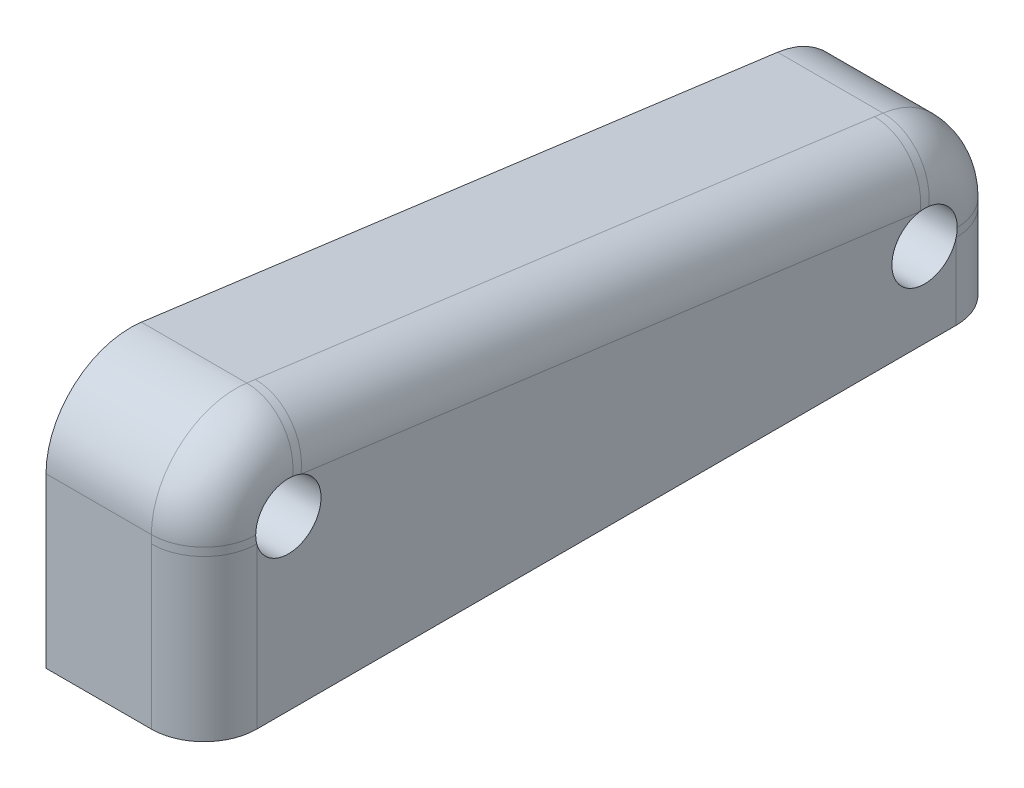
SolidWorks part; units mm, degrees
ref_plane "Plan de face" through (0, 0, 0) normal (0, 0, 1) x (1, 0, 0)
ref_plane "Plan de dessus" through (0, 0, 0) normal (0, 1, 0) x (1, 0, 0)
ref_plane "Plan de droite" through (0, 0, 0) normal (1, 0, 0) x (0, 0, -1)
sketch "Esquisse1" plane through (0, 0, 0) normal (1, 0, 0) x (0, 0, -1)
  line L0 (0, 0) -> (-76.3723, 0)
  line L1 (-76.3723, 0) -> (-76.3723, 25.1202)
  line L2 (-76.3723, 25.1202) -> (0, 15)
  line L3 (0, 15) -> (0, 0)
  line L4 (-68.3723, 16) -> (-8, 8) construction
  circle A0 centre (-68.3723, 16) radius 3.1
  circle A1 centre (-8, 8) radius 3.1
  dimension "D1" = 6.2
  dimension "D2" = 60.9
  dimension "D3" = 8
  dimension "D4" = 8
  dimension "D5" = 8
  dimension "D6" = 8
  dimension "D7" = 15
extrude "Boss.-Extru.1" add sketch "Esquisse1" along normal blind 15
fillet "Congé1" radius 8 2 edges at (7.5, 15, 0) (7.5, 25.1202, 76.3723)
fillet "Congé2" radius 5 3 edges at (15, 3.9951, 0) (15, 7.9951, 76.3723) (15, 19.9208, 37.1352)
sketch "Esquisse2" plane through (0, 0, 0) normal (-1, 0, 0) x (0, 0, 1)
  line L0 (60.5168, 17.9755) -> (15.0698, 11.9532)
  line L3 (71.3723, 5) -> (71.3723, 8.476)
  line L4 (67.3214, 23.9208) -> (6.9491, 15.9208)
  line L5 (0, 7.9902) -> (0, 0)
  line L6 (0, 0) -> (76.3723, 0)
  line L7 (76.3723, 0) -> (76.3723, 15.9902)
  line L11 (76.3723, 14.7311) -> (76.3723, 15.9902)
  line L12 (8.4177, 11.0717) -> (7.6059, 10.9642)
  line L13 (67.9782, 18.9642) -> (7.6059, 10.9642) construction
  line L14 (0, 7.9902) -> (0, 0) construction
  line L15 (0, 0) -> (76.3723, 0) construction
  line L16 (15.524, 5) -> (71.3723, 5)
  line L17 (5, 5) -> (71.3723, 5) construction
  line L18 (5, 7.9902) -> (5, 5) construction
  line L19 (76.3723, 0) -> (76.3723, 15.9902) construction
  line L20 (67.3214, 23.9208) -> (6.9491, 15.9208) construction
  line L21 (71.3723, 5) -> (71.3723, 15.9902) construction
  arc A2 (6.9491, 15.9208) -> (0, 7.9902) centre (8, 7.9902) ccw
  arc A3 (76.3723, 15.9902) -> (67.3214, 23.9208) centre (68.3723, 15.9902) ccw
  arc A10 (15.524, 5) -> (15.0698, 11.9532) centre (8, 8) ccw
  arc A11 (60.5168, 17.9755) -> (71.3723, 8.476) centre (68.3723, 16) ccw
  arc A14 (7.6059, 10.9642) -> (5, 7.9902) centre (8, 7.9902) ccw construction
  arc A15 (6.9491, 15.9208) -> (0, 7.9902) centre (8, 7.9902) ccw construction
  arc A16 (76.3723, 15.9902) -> (67.3214, 23.9208) centre (68.3723, 15.9902) ccw construction
  arc A17 (71.3723, 15.9902) -> (67.9782, 18.9642) centre (68.3723, 15.9902) ccw construction
  dimension "D1" = 0
  dimension "D2" = 5
extrude "Enlèv. mat.-Extru.1" cut sketch "Esquisse2" against normal blind 10 contours A11 L0 A10 L16 L3
